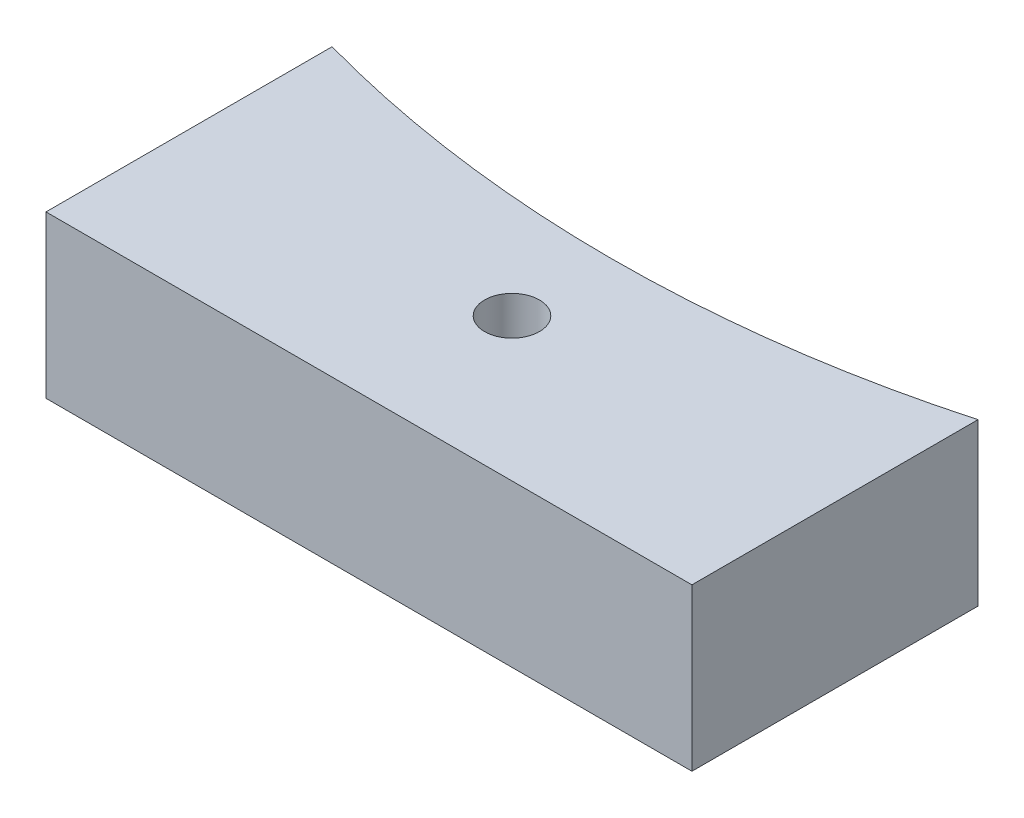
SolidWorks part; units mm, degrees
ref_plane "Ön Düzlem" through (0, 0, 0) normal (0, 0, 1) x (1, 0, 0)
ref_plane "Üst Düzlem" through (0, 0, 0) normal (0, 1, 0) x (1, 0, 0)
ref_plane "Sağ Düzlem" through (0, 0, 0) normal (1, 0, 0) x (0, 0, -1)
sketch "Çizim1" plane through (0, 0, 0) normal (0, 0, 1) x (1, 0, 0)
  line L0 (150, 70) -> (0, 70)
  line L1 (0, 70) -> (0, 0)
  line L2 (0, 0) -> (150, 0)
  line L3 (150, 0) -> (150, 70)
  line L4 (0, 70) -> (0, 0) construction
revolve "Döndür1" add sketch "Çizim1" angle 360 about L4
ref_plane "Düzlem1" through (0, 0, 180) normal (0, 0, 1) x (1, 0, 0)
sketch "Çizim2" plane through (0, 0, 180) normal (0, 0, 1) x (1, 0, 0)
  line L0 (-40, 0) -> (40, 0)
  line L1 (40, 0) -> (40, 40)
  line L2 (40, 40) -> (-40, 40)
  line L3 (-40, 40) -> (-40, 0)
extrude "Yükseklik-Ekstrüzyon1" add sketch "Çizim2" against normal up to next
ref_plane "Düzlem2" through (0, 0, -180) normal (0, 0, -1) x (-1, 0, 0)
hole_wizard "Delik1" positions "Çizim6" profile "Çizim5" legacy
sketch "Çizim6" plane through (0, 70, 0) normal (0, 1, 0) x (1, 0, 0)
  point P0 (0, 0)
sketch "Çizim5" plane through (0, 70, 0) normal (1, 0, 0) x (0, 0, 1)
  line L0 (0, 0) -> (0, 70)
  line L1 (0, 70) -> (130, 70)
  line L2 (130, 70) -> (130, 0)
  line L3 (130, 0) -> (0, 0)
  line L4 (0, 110) -> (0, -10) construction
  dimension "Diameter" = 260
  dimension "Depth" = 70
hole_wizard "Ø6.8 (6.8) Çap Delik1" positions "Çizim8" profile "Çizim7" hole size "Ø6.8" standard "ANSI Metrik"
sketch "Çizim8" plane through (0, 40, 0) normal (0, 1, 0) x (1, 0, 0)
  point P0 (0, -162.2842)
  point P1 (0, 162.2842)
sketch "Çizim7" plane through (0, 40, 162.2842) normal (1, 0, 0) x (0, 0, 1)
  line L0 (0, 0) -> (0, 40)
  line L1 (0, 40) -> (3.4, 40)
  line L2 (3.4, 40) -> (3.4, 0)
  line L5 (3.4, 0) -> (0, 0)
  line L11 (0, -6.35) -> (0, 107.95) construction
  dimension "Thru Hole Dia." = 6.8
  dimension "Thru Hole Depth" = 40
sketch "Çizim10" plane through (0, 70, 0) normal (0, 1, 0) x (1, 0, 0)
  circle A0 centre (0, 0) radius 150
  circle A1 centre (0, 0) radius 130
extrude "Kes-Ekstrüzyon2" cut sketch "Çizim10" against normal blind 70
sketch "Çizim11" plane through (0, 0, 0) normal (0, -1, 0) x (1, 0, 0)
  line L3 (40, 144.5683) -> (40, 180)
  line L4 (40, 180) -> (-40, 180)
  line L5 (-40, 180) -> (-40, 144.5683)
  line L6 (40, 144.5683) -> (40, 180)
  line L7 (40, 180) -> (-40, 180)
  line L8 (-40, 180) -> (-40, 144.5683)
  arc A1 (40, 144.5683) -> (-40, 144.5683) centre (0, 0) ccw
  arc A2 (40, 144.5683) -> (-40, 144.5683) centre (0, 0) ccw
  dimension "D1" = 0
extrude "Kes-Ekstrüzyon3" cut sketch "Çizim11" against normal blind 20
